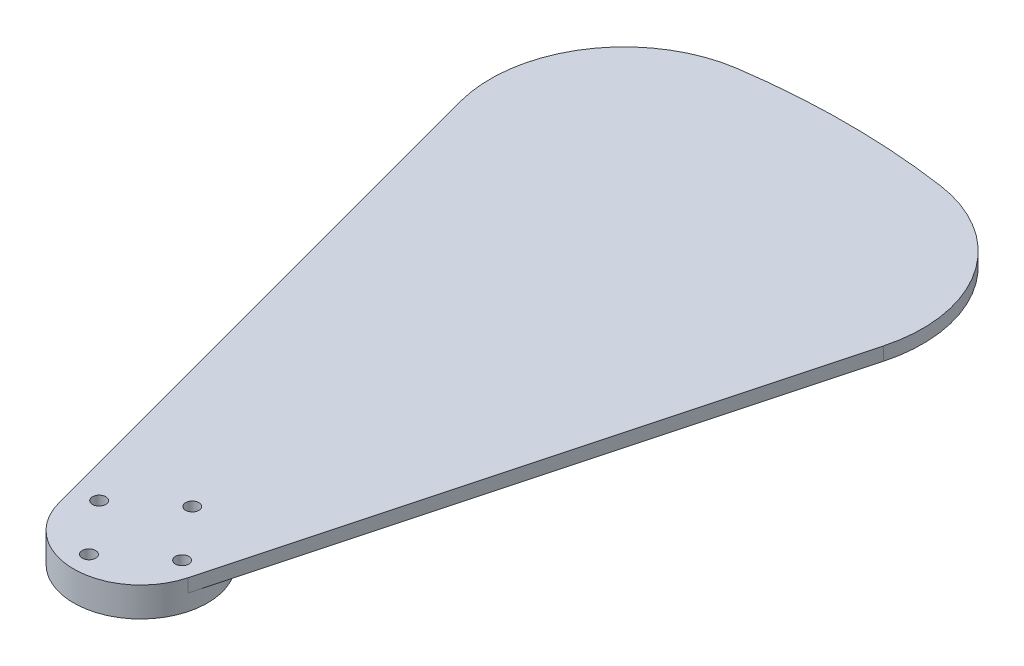
SolidWorks part; units mm, degrees
ref_plane "前视基准面" through (0, 0, 0) normal (0, 0, 1) x (1, 0, 0)
ref_plane "上视基准面" through (0, 0, 0) normal (0, 1, 0) x (1, 0, 0)
ref_plane "右视基准面" through (0, 0, 0) normal (1, 0, 0) x (0, 0, -1)
other "Configuration Table"
ref_plane "基准面1" through (0, 2.4, 0) normal (0, -1, 0) x (1, 0, 0)
sketch "草图1" plane through (0, 2.4, 0) normal (0, -1, 0) x (1, 0, 0)
  line L0 (36.8353, -98.834) -> (9.6593, 2.5882)
  line L1 (-9.6593, 2.5882) -> (-36.8353, -98.834)
  arc A0 (-36.8353, -98.834) -> (36.8353, -98.834) centre (0, 0) ccw
  arc A1 (9.6593, 2.5882) -> (-9.6593, 2.5882) centre (0, 0) ccw
extrude "凸台-拉伸1" add sketch "草图1" against normal blind 2
sketch "草图2" plane through (0, 2.4, 0) normal (0, -1, 0) x (1, 0, 0)
  circle A0 centre (0, 0) radius 10
extrude "凸台-拉伸2" add sketch "草图2" along normal blind 2.4
hole_wizard "Ø2.0 (2) 直径孔1" positions "草图4" profile "草图3" hole size "Ø2.0" standard "ANSI Metric"
sketch "草图4" plane through (0, 0, 0) normal (0, -1, 0) x (-1, 0, 0)
  point P0 (-6.9584, -0.7621)
  point P1 (-0.7621, 6.9584)
  point P2 (0.7621, -6.9584)
  point P3 (6.9584, 0.7621)
sketch "草图3" plane through (6.9584, 0, 0.7621) normal (1, 0, 0) x (0, 0, -1)
  line L0 (0, 0) -> (0, 4.4)
  line L1 (0, 4.4) -> (1, 4.4)
  line L2 (1, 4.4) -> (1, 0)
  line L5 (1, 0) -> (0, 0)
  line L11 (0, -6.35) -> (0, 107.95) construction
  dimension "通孔孔直径" = 2
  dimension "通孔孔深度" = 4.4
fillet "圆角1" radius 20 2 edges at (36.8353, 3.4, -98.834) (-36.8353, 3.4, -98.834)
